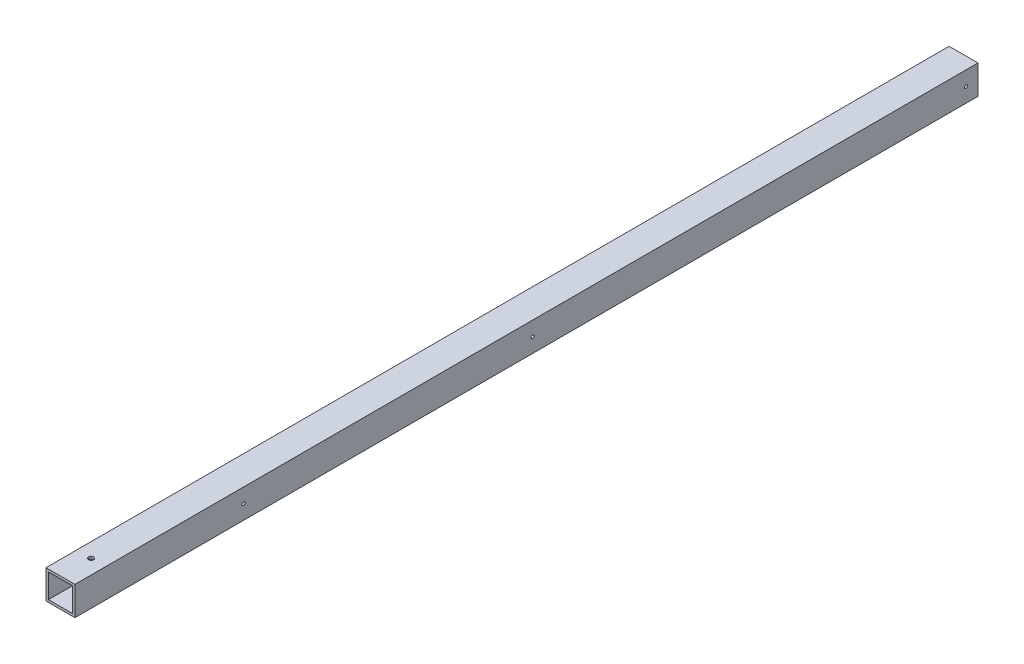
SolidWorks part; units mm, degrees
ref_plane "前视基准面" through (0, 0, 0) normal (0, 0, 1) x (1, 0, 0)
ref_plane "上视基准面" through (0, 0, 0) normal (0, 1, 0) x (1, 0, 0)
ref_plane "右视基准面" through (0, 0, 0) normal (1, 0, 0) x (0, 0, -1)
sketch "草图1" plane through (0, 0, 0) normal (0, 0, 1) x (1, 0, 0)
  line L0 (-12, 12) -> (12, 12)
  line L1 (-10, 10) -> (10, 10)
  line L2 (-10, 10) -> (-10, -10)
  line L3 (-10, -10) -> (10, -10)
  line L4 (10, 10) -> (10, -10)
  line L5 (-10, 10) -> (10, -10) construction
  line L6 (-10, -10) -> (10, 10) construction
  line L7 (12, 12) -> (12, -12)
  line L8 (-12, -12) -> (12, -12)
  line L9 (-12, 12) -> (-12, -12)
  point P0 (0, 0)
  dimension "D1" = 20
  dimension "D2" = 20
  dimension "D3" = 2
extrude "凸台-拉伸1" add sketch "草图1" along normal mid plane 750
sketch "草图2" plane through (-12, 0, 0) normal (-1, 0, 0) x (0, 0, 1)
  line L0 (-375, 12) -> (-375, -12) construction
  line L1 (375, 12) -> (375, -12) construction
  circle A0 centre (-365, 0) radius 2 construction
  circle A1 centre (-5, 0) radius 2 construction
  circle A2 centre (235, 0) radius 2 construction
  dimension "D1" = 10
  dimension "D2" = 370
  dimension "D3" = 140
hole_wizard "M3 螺纹孔的螺纹孔钻头1" positions "3D草图1" profile "草图3" hole size "M3" standard "GB" end condition through all
sketch3d "3D草图1"
  point P0 (-12, 0, -365)
  point P3 (-12, 0, -5)
  point P6 (-12, 0, 235)
sketch "草图3" plane through (-12, 0, -365) normal (0, 1, 0) x (0, 0, 1)
  line L0 (0, 0) -> (0, 24)
  line L1 (0, 24) -> (1.25, 24)
  line L2 (1.25, 24) -> (1.25, 0)
  line L5 (1.25, 0) -> (0, 0)
  line L11 (0, -6.35) -> (0, 107.95) construction
  dimension "通孔孔直径" = 2.5
  dimension "通孔孔深度" = 24
sketch "草图4" plane through (0, 12, 0) normal (0, 1, 0) x (1, 0, 0)
  line L0 (0, -1000) -> (0, 49000) construction
  line L1 (12, -375) -> (-12, -375) construction
  circle A0 centre (0, -349.5) radius 2
  dimension "D1" = 25.5
hole_wizard "M5 螺纹孔的螺纹孔钻头1" positions "3D草图2" profile "草图5" hole size "M5" standard "GB"
sketch3d "3D草图2"
  point P0 (0, 12, 349.5)
sketch "草图5" plane through (0, 12, 349.5) normal (1, 0, 0) x (0, 0, 1)
  line L0 (0, 0) -> (0, 11.2618)
  line L1 (0, 11.2618) -> (2.1, 10)
  line L2 (2.1, 10) -> (2.1, 0)
  line L5 (2.1, 0) -> (0, 0)
  line L10 (0, 11.2618) -> (-2.1, 10) construction
  line L11 (0, -6.35) -> (0, 107.95) construction
  dimension "孔直径" = 4.2
  dimension "孔深度" = 10
  dimension "导头角度" = 118
